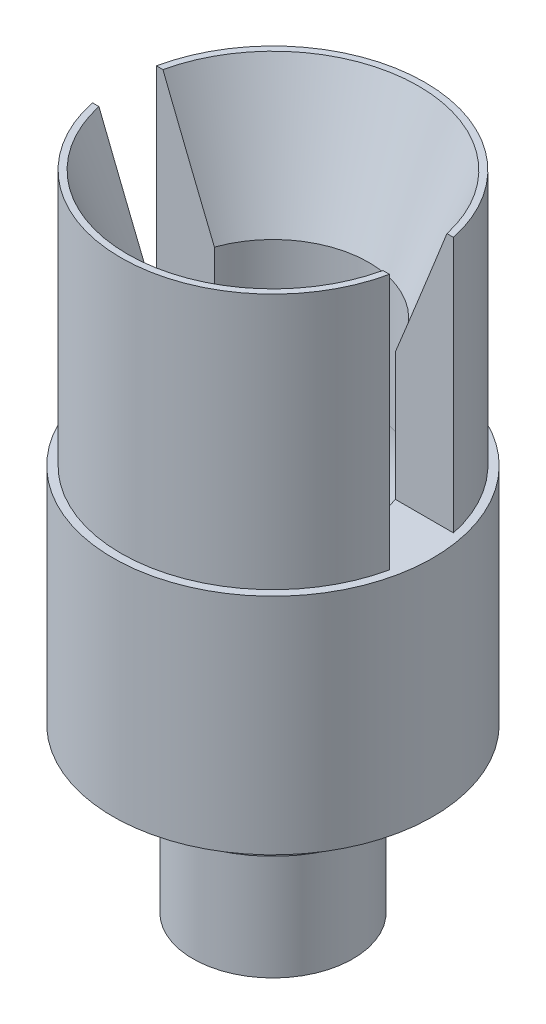
SolidWorks part; units mm, degrees
ref_plane "Plan de face" through (0, 0, 0) normal (0, 0, 1) x (1, 0, 0)
ref_plane "Plan de dessus" through (0, 0, 0) normal (0, 1, 0) x (1, 0, 0)
ref_plane "Plan de droite" through (0, 0, 0) normal (1, 0, 0) x (0, 0, -1)
sketch "Esquisse1" plane through (0, 0, 0) normal (0, 0, 1) x (1, 0, 0)
  line L0 (0, -1.2926) -> (0, 15.0866) construction
  line L1 (0, 0) -> (-2.5, 0)
  line L2 (-5, 5.1) -> (-5, 12.1)
  line L3 (-5, 12.1) -> (-4.75, 12.1)
  line L4 (-4.75, 12.1) -> (-4.75, 20.1)
  line L5 (-4.75, 20.1) -> (-4.55, 20.1)
  line L6 (-4.55, 20.1) -> (-3, 16.1)
  line L7 (-3, 16.1) -> (-3, 12.1)
  line L8 (0, 0) -> (0, 9.1)
  line L9 (-3.5, 5.1) -> (-5, 5.1)
  line L10 (-3.5, 4) -> (-3.5, 5.1)
  line L11 (-2.5, 4) -> (-3.5, 4)
  line L12 (-2.5, 0) -> (-2.5, 4)
  arc A0 (-3, 12.1) -> (0, 9.1) centre (0, 12.1) ccw
  dimension "D1" = 10
  dimension "D4" = 3
  dimension "D2" = 7
  dimension "D3" = 8
  dimension "D5" = 4
  dimension "D6" = 9.5
  dimension "D7" = 0.2
  dimension "D8" = 11
  dimension "D9" = 7
  dimension "D10" = 1.1
  dimension "D11" = 5
  dimension "D12" = 4
revolve "Révolution1" add sketch "Esquisse1" angle 360 about L0
sketch "Esquisse2" plane through (0, 0, 0) normal (1, 0, 0) x (0, 0, -1)
  line L0 (4.55, 20.1) -> (-4.55, 20.1) construction
  line L1 (-1, 12.1) -> (1, 12.1)
  line L2 (-1, 12.1) -> (-1, 20.1)
  line L3 (-1, 20.1) -> (1, 20.1)
  line L4 (1, 12.1) -> (1, 20.1)
  line L5 (-1, 12.1) -> (1, 20.1) construction
  line L6 (-1, 20.1) -> (1, 12.1) construction
  point P0 (0, 16.1)
  dimension "D1" = 2
  dimension "D2" = 8
extrude "Enlèv. mat.-Extru.1" cut sketch "Esquisse2" against normal up to next and the other way up to next
